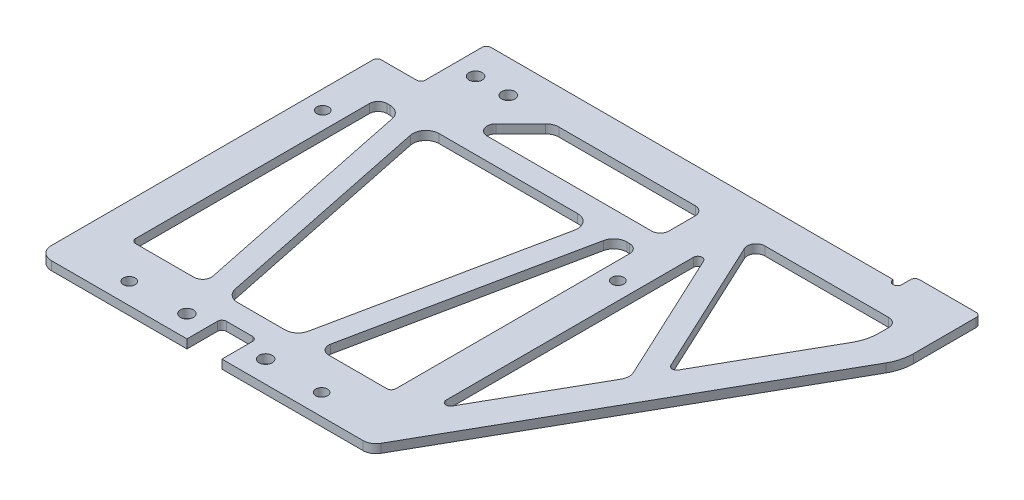
SolidWorks part; units mm, degrees
material "Thornel Mat VMA"
ref_plane "前视基准面" through (0, 0, 0) normal (0, 0, 1) x (1, 0, 0)
ref_plane "上视基准面" through (0, 0, 0) normal (0, 1, 0) x (1, 0, 0)
ref_plane "右视基准面" through (0, 0, 0) normal (1, 0, 0) x (0, 0, -1)
sketch "草图1" plane through (0, 0, 0) normal (0, 1, 0) x (1, 0, 0)
  line L0 (5, -7.5) -> (12.5, -7.5) construction
  line L1 (0, 0) -> (95, 0)
  line L2 (0, 0) -> (0, -15)
  line L3 (-10, -92.5) -> (66, -92.5)
  line L19 (95, 0) -> (95, 3)
  line L22 (110, -15) -> (110, 3)
  line L23 (95, 3) -> (110, 3)
  line L24 (0, -15) -> (-10, -15)
  line L25 (-10, -15) -> (-10, -92.5)
  line L26 (110, -15) -> (66, -92.5)
  circle A0 centre (5, -7.5) radius 1.5
  circle A1 centre (12.5, -7.5) radius 1.5
  dimension "D4" = 3
  dimension "D5" = 5
  dimension "D6" = 7.5
  dimension "D11" = 76
  dimension "D10" = 10
  dimension "D1" = 3
  dimension "D2" = 92.5
  dimension "D3" = 7.5
  dimension "D7" = 15
  dimension "D8" = 110
  dimension "D9" = 15
extrude "凸台-拉伸1" add sketch "草图1" along normal blind 2
sketch "草图4" plane through (0, 2, 0) normal (0, 1, 0) x (1, 0, 0)
  line L5 (28, -3.7432) -> (28, -87.7) construction
  line L6 (-10, -15) -> (-10, -92.5) construction
  line L23 (-5.75, -31.7) -> (61.75, -31.7) construction
  line L24 (-5.75, -31.7) -> (6, -87.7) construction
  line L25 (6, -87.7) -> (50, -87.7) construction
  line L27 (-10, -92.5) -> (66, -92.5) construction
  line L28 (-10, -92.5) -> (66, -92.5) construction
  line L29 (24, -84.5) -> (32, -84.5)
  line L30 (24, -84.5) -> (24, -92.5)
  line L31 (24, -92.5) -> (32, -92.5)
  line L32 (32, -84.5) -> (32, -92.5)
  circle A4 centre (-5.75, -31.7) radius 1.35
  circle A5 centre (6, -87.7) radius 1.35
  circle A8 centre (50, -87.7) radius 1.35
  circle A9 centre (61.75, -31.7) radius 1.35
  circle A10 centre (19, -87.5) radius 1.5
  circle A11 centre (37, -87.5) radius 1.5
  point P8 (28, -31.7)
  point P17 (28, -84.5)
  dimension "D7" = 44
  dimension "D8" = 2.7
  dimension "D4" = 38
  dimension "D9" = 3
  dimension "D10" = 5
  dimension "D11" = 5
  dimension "D1" = 56
  dimension "D2" = 67.5
  dimension "D3" = 4.8
  dimension "D5" = 8
  dimension "D6" = 3.2
extrude "切除-拉伸2" cut sketch "草图4" against normal through all
sketch "草图5" plane through (0, 2, 0) normal (0, 1, 0) x (1, 0, 0)
  line L0 (95, 0) -> (0, 0) construction
  circle A0 centre (94, 0) radius 1
  dimension "D1" = 2
extrude "切除-拉伸3" cut sketch "草图5" against normal through all
fillet "圆角4" radius 1 2 edges at (110, 1, -3) (95, 1, -3)
sketch "草图2" plane through (0, 2, 0) normal (0, 1, 0) x (1, 0, 0)
  line L21 (66, -92.5) -> (110, -15) construction
  line L24 (-1.75, -23) -> (57.75, -23)
  line L27 (-1.75, -23) -> (-1.75, -79.5)
  line L28 (65.75, -78.7623) -> (102, -14.9128)
  line L29 (102, -8) -> (65.75, -8)
  line L40 (102, -8) -> (102, -14.9128)
  line L41 (65.75, -78.7623) -> (65.75, -8)
  line L50 (-1.75, -79.5) -> (57.75, -79.5)
  line L51 (57.75, -23) -> (57.75, -79.5)
  line L55 (32, -84.5) -> (24, -84.5) construction
  line L58 (93, 0) -> (0, 0) construction
  line L59 (110, -15) -> (110, 2) construction
  line L60 (0, -15) -> (-10, -15) construction
  line L62 (23.3137, -8) -> (57.75, -8)
  line L63 (23.3137, -8) -> (13.3137, -18)
  line L64 (13.3137, -18) -> (57.75, -18)
  line L65 (57.75, -8) -> (57.75, -18)
  circle A1 centre (12.5, -7.5) radius 1.5 construction
  circle A4 centre (-5.75, -31.7) radius 1.35 construction
  circle A6 centre (61.75, -31.7) radius 1.35 construction
  dimension "D1" = 7
  dimension "D2" = 4
  dimension "D11" = 8
  dimension "D3" = 4
  dimension "D8" = 4
  dimension "D4" = 5
  dimension "D5" = 8
  dimension "D6" = 8
  dimension "D7" = 8
  dimension "D9" = 5
  dimension "D10" = 8
  dimension "D12" = 45
extrude "切除-拉伸1" cut sketch "草图2" against normal through all
sketch "草图3" plane through (0, 2, 0) normal (0, 1, 0) x (1, 0, 0)
  line L0 (84.9126, -49.0609) -> (65.75, -8)
  line L1 (5.5, -21) -> (18, -81.5)
  line L2 (57.75, -23) -> (-1.75, -23) construction
  line L4 (28, -79.5) -> (28, -23) construction
  line L5 (-1.75, -79.5) -> (57.75, -79.5) construction
  line L6 (50.5, -21) -> (38, -81.5)
  line L7 (65.75, -78.7623) -> (102, -14.9128) construction
  point P9 (83.875, -46.8376)
  dimension "D1" = 2
  dimension "D2" = 2
  dimension "D3" = 45
  dimension "D4" = 20
  dimension "D5" = 2
extrude "拉伸-薄壁1" add sketch "草图3" against normal up to surface (2 mm away) thin up to face at (83.875, 0, 27.4188) thin type mid plane wall 5
fillet "圆角1" radius 1 10 edges at (0, 1, 0) (57.75, 1, 79.5) (-1.75, 1, 79.5) (32, 1, 84.5) (24, 1, 84.5) (85.3892, 1, 44.1705) (65.75, 1, 13.9115) (-10, 1, 15) (0, 1, 15) (65.75, 1, 78.7623)
fillet "圆角3" radius 3 10 edges at (8.466, 1, 23) (20.1396, 1, 79.5) (47.534, 1, 23) (35.8604, 1, 79.5) (52.6396, 1, 23) (3.3604, 1, 23) (23.3137, 1, 8) (66, 1, 92.5) (-10, 1, 92.5) (82.3608, 1, 49.5046)
fillet "圆角2" radius 2 9 edges at (15.034, 1, 79.5) (40.966, 1, 79.5) (57.75, 1, 23) (-1.75, 1, 23) (68.5088, 1, 8) (102, 1, 8) (13.3137, 1, 18) (57.75, 1, 8) (57.75, 1, 18)
fillet "圆角5" radius 10 2 edges at (102, 1, 14.9128) (110, 1, 15)
